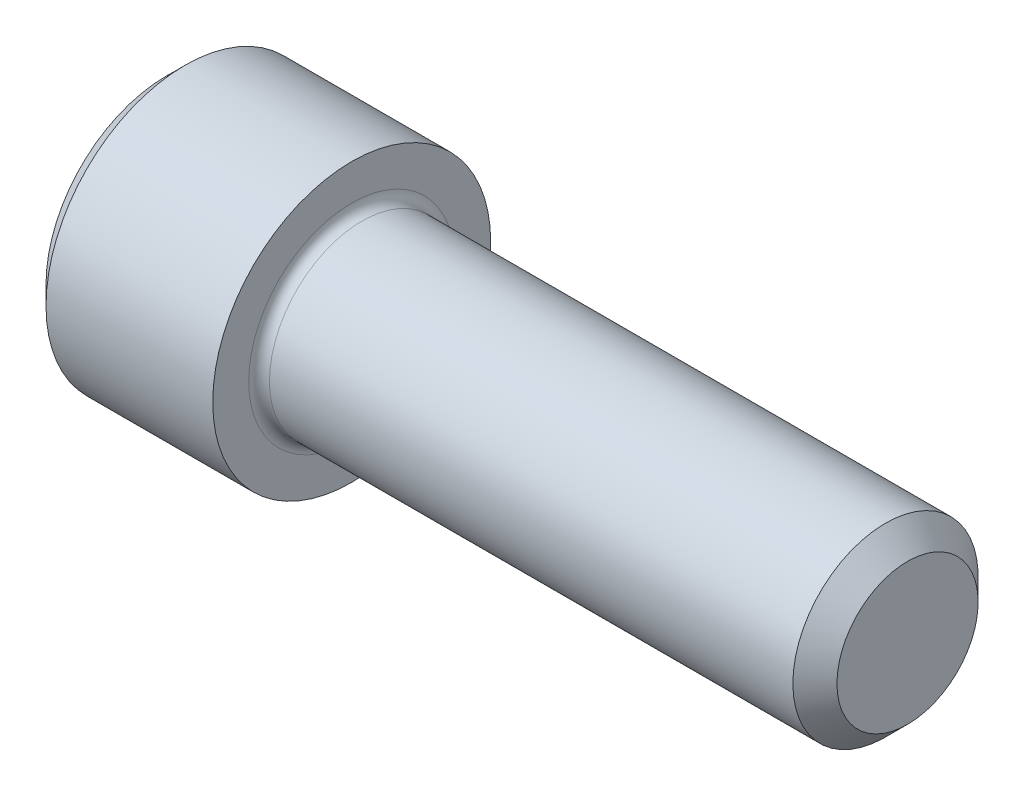
SolidWorks part; units mm, degrees
ref_plane "Plane1" through (0, 0, 0) normal (0, 0, 1) x (1, 0, 0)
ref_plane "Plane2" through (0, 0, 0) normal (0, 1, 0) x (1, 0, 0)
ref_plane "Plane3" through (0, 0, 0) normal (1, 0, 0) x (0, 0, -1)
sketch "BodySke" plane through (0, 0, 0) normal (0, 0, 1) x (1, 0, 0)
  line L0 (0, 0) -> (0, 4.1275)
  line L1 (0.635, 4.7625) -> (6.35, 4.7625)
  line L2 (6.35, 4.7625) -> (6.35, 3.175)
  line L3 (6.35, 3.175) -> (24.6443, 3.175)
  line L4 (25.4, 2.4193) -> (25.4, 0)
  line L5 (25.4, 0) -> (0, 0)
  line L6 (-31.75, 0) -> (127, 0) construction
  line L7 (0, 4.1275) -> (0.635, 4.7625)
  line L8 (25.4, 2.4193) -> (24.6443, 3.175)
  line L9 (0, -4.1275) -> (0.635, -4.7625) construction
  line L10 (25.4, -2.4193) -> (24.6444, -3.175) construction
  line L11 (7.62, 9.525) -> (7.62, 3.175) construction
  line L12 (6.35, 9.525) -> (6.35, 3.175) construction
  line L13 (-12.7, 9.525) -> (-12.7, 3.175) construction
  dimension "Diameter" = 6.35
  dimension "Head_ht" = 6.35
  dimension "Length" = 19.05
  dimension "Body_ch_ang" = 45
  dimension "Head_dia" = 9.525
  dimension "Head_ch_ang" = 45
  dimension "Head_side_ht" = 5.715
  dimension "Minor_dia" = 4.8387
  dimension "Advance" = 1.27
  dimension "Thread_nom" = 19.05
  dimension "Thread_length" = 38.1
revolve "Base-Revolve" add sketch "BodySke"
cosmetic thread "ThreadCosmetic" [suppressed]
fillet "Fillet1" radius 0.3556 1 edges at (6.35, 0, 3.175)
sketch "Sketch2" plane through (0, 0, 0) normal (0, 0, 1) x (1, 0, 0)
  line L0 (0, 2.3812) -> (3.048, 2.3812)
  line L1 (3.048, 2.3812) -> (4.4228, 0)
  line L2 (-31.75, 0) -> (127, 0) construction
  line L3 (4.4228, 0) -> (0, 0)
  line L4 (0, 0) -> (0, 2.3812)
  line L5 (0, 4.1275) -> (0, -4.1275) construction
  line L6 (0, 0) -> (47.625, 0) construction
  line L7 (6.35, -4.7625) -> (6.35, 4.7625) construction
  dimension "D1" = 2.3813
  dimension "D2" = 60
  dimension "Wall_thickness" = 3.302
revolve "Hex-PreBroach" cut sketch "Sketch2" angle 360 about L6
sketch "Sketch3" plane through (0, 0, 0) normal (-1, 0, 0) x (0, 0.5, 0.866)
  line L0 (1.3748, 2.3813) -> (-1.3748, 2.3813)
  line L1 (-1.3748, 2.3813) -> (-2.7496, 0)
  line L2 (1.3748, 2.3813) -> (2.7496, 0)
  line L3 (1.3748, -2.3812) -> (2.7496, 0)
  line L4 (1.3748, -2.3812) -> (-1.3748, -2.3812)
  line L5 (-1.3748, -2.3812) -> (-2.7496, 0)
  dimension "D1" = 2.3813
  dimension "D2" = 2.3813
  dimension "Hex_size" = 4.7625
extrude "Hex" cut sketch "Sketch3" against normal blind 3.048
sketch "Sketch4" plane through (0, 0, 0) normal (-1, 0, 0) x (0, 0, 1)
  line L0 (0, 0) -> (2.8067, 0)
  line L1 (0, 0) -> (6.1484, 3.5498) construction
  line L2 (0, 0) -> (1.4033, 2.4307)
  line L3 (2.3336, 0.614) -> (2.6851, 0.817)
  line L4 (1.6986, 1.7139) -> (2.0501, 1.9169)
  arc A0 (2.3336, 0.614) -> (1.6986, 1.7139) centre (0, 0) ccw
  arc A1 (2.8067, 0) -> (2.6851, 0.817) centre (0, 0) ccw
  arc A2 (1.4033, 2.4307) -> (2.0501, 1.9169) centre (0, 0) cw
  dimension "D1" = 30
  dimension "Spline_n_dim" = 4.826
  dimension "Spline_m_dim" = 5.6134
  dimension "D2" = 60
  dimension "D3" = 0.635
  dimension "Spline_p_dim" = 1.27
extrude "Spline" [suppressed] cut sketch "Sketch4" against normal blind 3.048
pattern_circular "CirPattern1" [suppressed] count 6 every 60
sketch "Sketch5" plane through (0, 0, 0) normal (0, 0, 1) x (1, 0, 0)
  line L0 (-31.75, 0) -> (127, 0) construction
  line L2 (0, 4.1275) -> (0, -4.1275) construction
  circle A0 centre (2.159, 0) radius 0.5905
  dimension "Drilled_hole_dia" = 1.1811
  dimension "Drilled_hole_loc" = 2.159
extrude "Hole" [suppressed] cut sketch "Sketch5" against normal through all and the other way through all
pattern_circular "Drilled-4" [suppressed] count 2 every 60
pattern_circular "Drilled-6" [suppressed] count 3 every 60
sketch "ThdSchSke" plane through (0, 0, 0) normal (0, 0, 1) x (1, 0, 0)
  line L0 (7.62, -2.4193) -> (7.0909, -3.175)
  line L1 (7.62, -2.4193) -> (8.1491, -3.175)
  line L2 (8.1491, -3.175) -> (8.1491, -3.9688)
  line L3 (-3.175, 0) -> (5.1513, 0) construction
  line L5 (8.1491, -3.9688) -> (7.0909, -3.9688)
  line L6 (7.0909, -3.9688) -> (7.0909, -3.175)
  line L7 (0, 4.1275) -> (0, -4.1275) construction
  dimension "Thread_minor" = 4.8387
  dimension "Diameter" = 6.35
  dimension "Start" = 7.62
  dimension "SideAngle" = 55
  dimension "VeeAngle" = 70
  dimension "Overcut" = 7.9375
revolve "ThreadSchematic" [suppressed] cut sketch "ThdSchSke" angle 360 about L3
pattern_linear "ThdSchPat" [suppressed]
equation "\"D2@Sketch3\" = \"Hex_size@Sketch3\" / 2"
equation "\"D1@Sketch3\" = \"Hex_size@Sketch3\" / 2"
equation "\"D1@Sketch2\" = \"Hex_size@Sketch3\" / 2"
equation "\"D3@Sketch4\" = \"Spline_p_dim@Sketch4\" / 2"
equation "\"Thread_minor@ThreadCosmetic\"  =  \"Minor_dia@BodySke\""
equation "\"D2@CirPattern1\" = 360 / \"Num_teeth@CirPattern1\""
equation "\"Wall_thickness@Sketch2\" = \"Head_ht@BodySke\" - \"Key_eng@Hex\""
equation "\"Thread_length@ThreadCosmetic\" = ((sgn( (\"Length@BodySke\" - \"Advance@BodySke\" ) - \"Thread_nom@BodySke\" )-1)*( (\"Length@BodySke\" - \"Advance@BodySke\" ) - \"Thread_nom@BodySke\" ))/-2+ \"Thread_nom@BodySke\""
equation "\"Thread_minor@ThdSchSke\" = \"Minor_dia@BodySke\""
equation "\"Diameter@ThdSchSke\" = \"Diameter@BodySke\""
equation "\"Overcut@ThdSchSke\" = \"Diameter@BodySke\" * 1.25"
equation "\"Start@ThdSchSke\" = \"Head_ht@BodySke\" + \"Length@BodySke\" - \"Thread_length@ThreadCosmetic\"  '---Non-countersunk---"
equation "\"Num_threads@ThdSchPat\" = int( \"Thread_length@ThreadCosmetic\" / \"Advance@BodySke\" + 0.999 )  + 1"
equation "\"Advance@ThdSchPat\" = \"Thread_length@ThreadCosmetic\" /  (\"Num_threads@ThdSchPat\" - 1) 'relax it"
equation "\"Num_threads@ThdSchPat\" = \"Num_threads@ThdSchPat\" - sgn( \"Num_threads@ThdSchPat\" - 1) '---chamfered tips only---"
